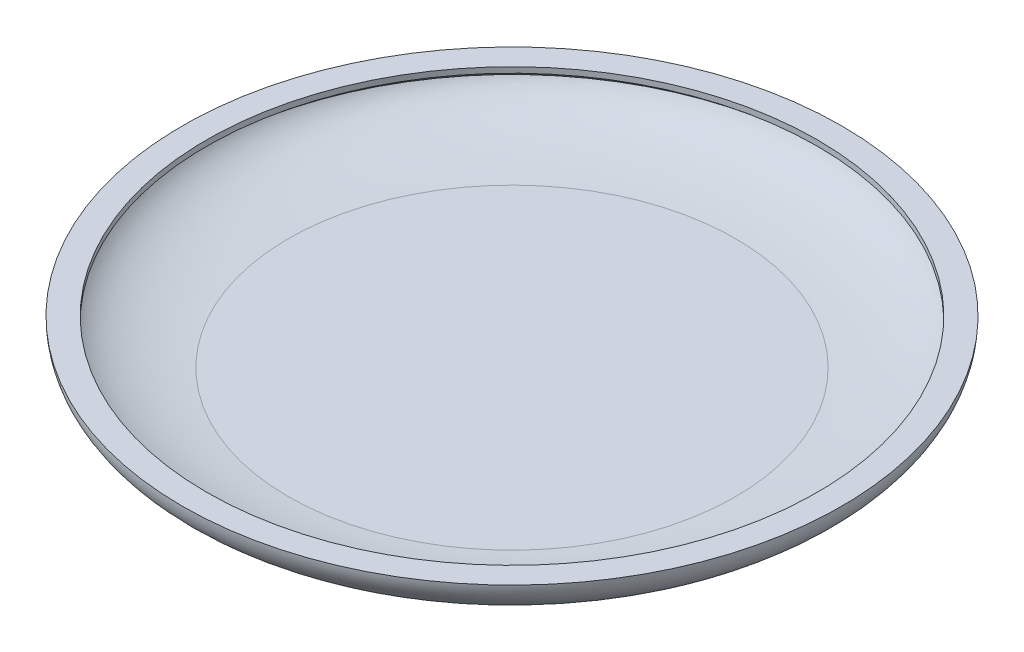
SolidWorks part; units mm, degrees
material "1060 Alloy"
ref_plane "Front Plane" through (0, 0, 0) normal (0, 0, 1) x (1, 0, 0)
ref_plane "Top Plane" through (0, 0, 0) normal (0, 1, 0) x (1, 0, 0)
ref_plane "Right Plane" through (0, 0, 0) normal (1, 0, 0) x (0, 0, -1)
sketch "Center axis" plane through (0, 0, 0) normal (0, 0, 1) x (1, 0, 0)
  line L0 (0, 26.6431) -> (0, -7.9832) construction
sketch3d "Lid lock plane" plane through (0, 0, 0) normal (0, 0, 1) x (1, 0, 0)
  dimension "D1" = 15
sketch "Body outline" plane through (0, 0, 0) normal (0, 0, 1) x (1, 0, 0)
  line L0 (0, 0) -> (-59.8117, 0)
  line L3 (-88.45, 14) -> (-81.95, 14)
  line L5 (-60, 2) -> (0, 2)
  line L6 (0, 2) -> (0, 0)
  line L9 (-81.95, 14) -> (-81.95, 12.5)
  line L10 (-81.95, 12.5) -> (-84.2714, 10.5517)
  spline S0 degree 2 poles (-60, 2) (-80.4732, 3.4204) (-84.2714, 10.5517) knots 0 0 0 1 1 1
  spline S1 degree 3 poles (-59.8117, 0) (-68.315, -0.0052) (-88.0009, 2.6451) (-88.45, 14) knots 0 0 0 0 1 1 1 1
  point P3 (-85.2012, 12.2998)
  point P4 (-88.45, 13.428)
  point P6 (-88.9497, 14)
  point P7 (0, 0)
  point P11 (0, 0)
  point P13 (0, 0)
  point P14 (-84.2714, 10.5517)
  point P15 (0, 0)
  point P16 (0, 0)
  point P17 (0, 0)
  point P18 (-83.0298, 12.1674)
  point P19 (0, 0)
  point P20 (-81.95, 12.3854)
  point P21 (0, 0)
  point P22 (0, 0)
  point P23 (0, 0)
  dimension "D1" = 6.5
  dimension "D2" = 1.5
  dimension "D3" = 3.4483
revolve "Revolve body" add sketch "Body outline" angle 360 about L0
